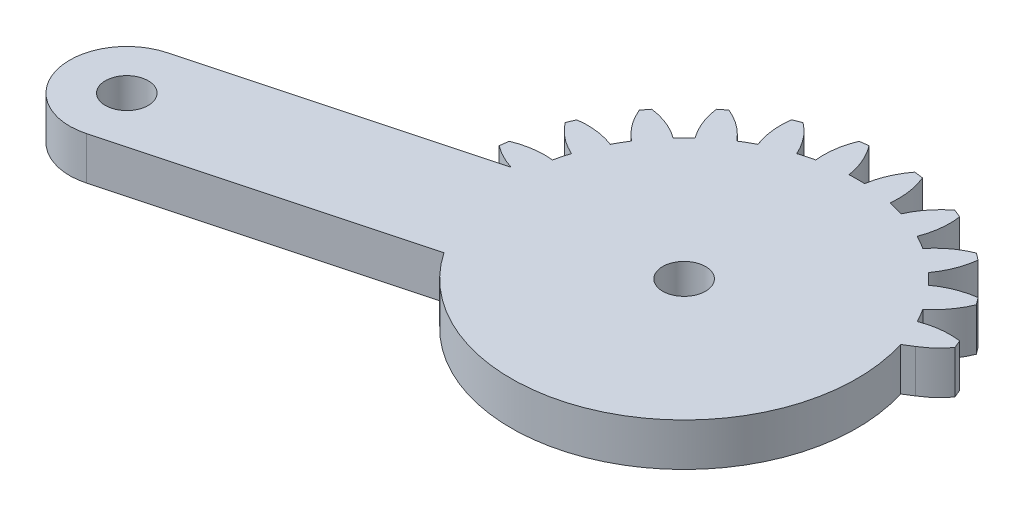
SolidWorks part; units mm, degrees
ref_plane "Front Plane" through (0, 0, 0) normal (0, 0, 1) x (1, 0, 0)
ref_plane "Top Plane" through (0, 0, 0) normal (0, 1, 0) x (1, 0, 0)
ref_plane "Right Plane" through (0, 0, 0) normal (1, 0, 0) x (0, 0, -1)
sketch "Sketch1" plane through (0, 0, 0) normal (0, 1, 0) x (1, 0, 0)
  line L0 (20.6437, 4) -> (2.0816, 4)
  line L1 (2.0816, -4) -> (20.6437, -4)
  arc A0 (2.0816, 4) -> (3.5217, 5.3071) centre (-0.7683, 8.5867) ccw
  arc A1 (3.5217, 5.3071) -> (3.2829, 5.8838) centre (-10.1063, 0) ccw
  arc A2 (3.2829, 5.8838) -> (0.6271, 5.5703) centre (2.5684, 0.5313) ccw
  arc A3 (0.6271, 5.5703) -> (0.0844, 6.5103) centre (-10.1063, 0) ccw
  arc A4 (0.0844, 6.5103) -> (1.6838, 8.6535) centre (-3.3089, 10.711) ccw
  arc A5 (1.6838, 8.6535) -> (1.3038, 9.1487) centre (-10.1063, 0) ccw
  arc A6 (1.3038, 9.1487) -> (-1.1803, 8.1585) centre (1.999, 3.7936) ccw
  arc A7 (-1.1803, 8.1585) -> (-1.9479, 8.926) centre (-10.1063, 0) ccw
  arc A8 (-1.9479, 8.926) -> (-0.9576, 11.4102) centre (-6.3127, 12.1053) ccw
  arc A9 (-0.9576, 11.4102) -> (-1.4528, 11.7901) centre (-10.1063, 0) ccw
  arc A10 (-1.4528, 11.7901) -> (-3.596, 10.1907) centre (0.6046, 6.7975) ccw
  arc A11 (-3.596, 10.1907) -> (-4.5361, 10.7334) centre (-10.1063, 0) ccw
  arc A12 (-4.5361, 10.7334) -> (-4.2225, 13.3892) centre (-9.5751, 12.6747) ccw
  arc A13 (-4.2225, 13.3892) -> (-4.7992, 13.6281) centre (-10.1063, 0) ccw
  arc A14 (-4.7992, 13.6281) -> (-6.4554, 11.5285) centre (-1.5196, 9.3381) ccw
  arc A15 (-6.4554, 11.5285) -> (-7.5039, 11.8094) centre (-10.1063, 0) ccw
  arc A16 (-7.5039, 11.8094) -> (-7.8884, 14.4558) centre (-12.8736, 12.3803) ccw
  arc A17 (-7.8884, 14.4558) -> (-8.5072, 14.5373) centre (-10.1063, 0) ccw
  arc A18 (-8.5072, 14.5373) -> (-9.5636, 12.0806) centre (-4.2291, 11.2423) ccw
  arc A19 (-9.5636, 12.0806) -> (-10.6491, 12.0806) centre (-10.1063, 0) ccw
  arc A20 (-10.6491, 12.0806) -> (-11.7054, 14.5373) centre (-15.9836, 11.2423) ccw
  arc A21 (-11.7054, 14.5373) -> (-12.3243, 14.4558) centre (-10.1063, 0) ccw
  arc A22 (-12.3243, 14.4558) -> (-12.7088, 11.8094) centre (-7.3391, 12.3803) ccw
  arc A23 (-12.7088, 11.8094) -> (-13.7573, 11.5285) centre (-10.1063, 0) ccw
  arc A24 (-13.7573, 11.5285) -> (-15.4135, 13.6281) centre (-18.6931, 9.3381) ccw
  arc A25 (-15.4135, 13.6281) -> (-15.9901, 13.3892) centre (-10.1063, 0) ccw
  arc A26 (-15.9901, 13.3892) -> (-15.6766, 10.7334) centre (-10.6376, 12.6747) ccw
  arc A27 (-15.6766, 10.7334) -> (-16.6166, 10.1907) centre (-10.1063, 0) ccw
  arc A28 (-16.6166, 10.1907) -> (-18.7599, 11.7901) centre (-20.8173, 6.7975) ccw
  arc A29 (-18.7599, 11.7901) -> (-19.255, 11.4102) centre (-10.1063, 0) ccw
  arc A30 (-19.255, 11.4102) -> (-18.2648, 8.926) centre (-13.9, 12.1053) ccw
  arc A31 (-18.2648, 8.926) -> (-19.0324, 8.1585) centre (-10.1063, 0) ccw
  arc A32 (-19.0324, 8.1585) -> (-21.5165, 9.1487) centre (-22.2117, 3.7936) ccw
  arc A33 (-21.5165, 9.1487) -> (-21.8965, 8.6535) centre (-10.1063, 0) ccw
  arc A34 (-21.8965, 8.6535) -> (-20.2971, 6.5103) centre (-16.9038, 10.711) ccw
  arc A35 (-20.2971, 6.5103) -> (-20.8398, 5.5703) centre (-10.1063, 0) ccw
  arc A36 (-20.8398, 5.5703) -> (-23.4956, 5.8838) centre (-22.7811, 0.5313) ccw
  arc A37 (-23.4956, 5.8838) -> (-23.7344, 5.3071) centre (-10.1063, 0) ccw
  arc A38 (-23.7344, 5.3071) -> (-21.6348, 3.6509) centre (-19.4444, 8.5867) ccw
  arc A39 (-21.6348, 3.6509) -> (-21.9157, 2.6025) centre (-10.1063, 0) ccw
  arc A40 (-21.9157, 2.6025) -> (-24.5622, 2.2179) centre (-22.4867, -2.7673) ccw
  arc A41 (-24.5622, 2.2179) -> (-24.6437, 1.5991) centre (-10.1063, 0) ccw
  arc A42 (-24.6437, 1.5991) -> (-22.1869, 0.5427) centre (-21.3486, 5.8773) ccw
  arc A43 (-22.1869, 0.5427) -> (-22.1869, -0.5427) centre (-10.1063, 0) ccw
  arc A44 (-22.1869, -0.5427) -> (-24.6437, -1.5991) centre (-21.3486, -5.8773) ccw
  arc A45 (-24.6437, -1.5991) -> (-24.5622, -2.2179) centre (-10.1063, 0) ccw
  arc A46 (-24.5622, -2.2179) -> (-21.9157, -2.6025) centre (-22.4867, 2.7673) ccw
  arc A47 (-21.9157, -2.6025) -> (-21.6348, -3.6509) centre (-10.1063, 0) ccw
  arc A48 (-21.6348, -3.6509) -> (-23.7344, -5.3071) centre (-19.4444, -8.5867) ccw
  arc A49 (-23.7344, -5.3071) -> (-23.4956, -5.8838) centre (-10.1063, 0) ccw
  arc A50 (-23.4956, -5.8838) -> (-20.8398, -5.5703) centre (-22.7811, -0.5313) ccw
  arc A51 (-20.8398, -5.5703) -> (-20.2971, -6.5103) centre (-10.1063, 0) ccw
  arc A52 (-20.2971, -6.5103) -> (-21.8965, -8.6535) centre (-16.9038, -10.711) ccw
  arc A53 (-21.8965, -8.6535) -> (-21.5165, -9.1487) centre (-10.1063, 0) ccw
  arc A54 (-21.5165, -9.1487) -> (-19.0324, -8.1585) centre (-22.2117, -3.7936) ccw
  arc A55 (-19.0324, -8.1585) -> (-18.2648, -8.926) centre (-10.1063, 0) ccw
  arc A56 (-18.2648, -8.926) -> (-19.255, -11.4102) centre (-13.9, -12.1053) ccw
  arc A57 (-19.255, -11.4102) -> (-18.7599, -11.7901) centre (-10.1063, 0) ccw
  arc A58 (-18.7599, -11.7901) -> (-16.6166, -10.1907) centre (-20.8173, -6.7975) ccw
  arc A59 (-16.6166, -10.1907) -> (-15.6766, -10.7334) centre (-10.1063, 0) ccw
  arc A60 (-15.6766, -10.7334) -> (-15.9901, -13.3892) centre (-10.6376, -12.6747) ccw
  arc A61 (-15.9901, -13.3892) -> (-15.4135, -13.6281) centre (-10.1063, 0) ccw
  arc A62 (-15.4135, -13.6281) -> (-13.7573, -11.5285) centre (-18.6931, -9.3381) ccw
  arc A63 (-13.7573, -11.5285) -> (-12.7088, -11.8094) centre (-10.1063, 0) ccw
  arc A64 (-12.7088, -11.8094) -> (-12.3243, -14.4558) centre (-7.3391, -12.3803) ccw
  arc A65 (-12.3243, -14.4558) -> (-11.7054, -14.5373) centre (-10.1063, 0) ccw
  arc A66 (-11.7054, -14.5373) -> (-10.6491, -12.0806) centre (-15.9836, -11.2423) ccw
  arc A67 (-10.6491, -12.0806) -> (-9.5636, -12.0806) centre (-10.1063, 0) ccw
  arc A68 (-9.5636, -12.0806) -> (-8.5072, -14.5373) centre (-4.2291, -11.2423) ccw
  arc A69 (-8.5072, -14.5373) -> (-7.8884, -14.4558) centre (-10.1063, 0) ccw
  arc A70 (-7.8884, -14.4558) -> (-7.5039, -11.8094) centre (-12.8736, -12.3803) ccw
  arc A71 (-7.5039, -11.8094) -> (-6.4554, -11.5285) centre (-10.1063, 0) ccw
  arc A72 (-6.4554, -11.5285) -> (-4.7992, -13.6281) centre (-1.5196, -9.3381) ccw
  arc A73 (-4.7992, -13.6281) -> (-4.2225, -13.3892) centre (-10.1063, 0) ccw
  arc A74 (-4.2225, -13.3892) -> (-4.5361, -10.7334) centre (-9.5751, -12.6747) ccw
  arc A75 (-4.5361, -10.7334) -> (-3.596, -10.1907) centre (-10.1063, 0) ccw
  arc A76 (-3.596, -10.1907) -> (-1.4528, -11.7901) centre (0.6046, -6.7975) ccw
  arc A77 (-1.4528, -11.7901) -> (-0.9576, -11.4102) centre (-10.1063, 0) ccw
  arc A78 (-0.9576, -11.4102) -> (-1.9479, -8.926) centre (-6.3127, -12.1053) ccw
  arc A79 (-1.9479, -8.926) -> (-1.1803, -8.1585) centre (-10.1063, 0) ccw
  arc A80 (-1.1803, -8.1585) -> (1.3038, -9.1487) centre (1.999, -3.7936) ccw
  arc A81 (1.3038, -9.1487) -> (1.6838, -8.6535) centre (-10.1063, 0) ccw
  arc A82 (1.6838, -8.6535) -> (0.0844, -6.5103) centre (-3.3089, -10.711) ccw
  arc A83 (0.0844, -6.5103) -> (0.6271, -5.5703) centre (-10.1063, 0) ccw
  arc A84 (0.6271, -5.5703) -> (3.2829, -5.8838) centre (2.5684, -0.5313) ccw
  arc A85 (3.2829, -5.8838) -> (3.5217, -5.3071) centre (-10.1063, 0) ccw
  arc A86 (3.5217, -5.3071) -> (2.0816, -4) centre (-0.7683, -8.5867) ccw
  arc A87 (20.6437, -4) -> (20.6437, 4) centre (20.6437, 0) ccw
  circle A88 centre (-10.1063, 0) radius 1.5
  circle A89 centre (20.6437, 0) radius 1.5
  dimension "D1" = 3
  dimension "D2" = 3
extrude "Boss-Extrude1" add sketch "Sketch1" along normal blind 3
sketch "Sketch3" plane through (0, 3, 0) normal (0, 1, 0) x (1, 0, 0)
  line L0 (-10.1063, 0) -> (-40.8563, 0) construction
  line L1 (-10.1063, 0) -> (-40.8563, -8.2394)
  line L2 (-11.1416, 3.8637) -> (-41.8916, -4.3757)
  line L3 (-9.0711, -3.8637) -> (-39.8211, -12.1031)
  circle A0 centre (-10.1063, 0) radius 1.5
  circle A1 centre (20.6437, 0) radius 1.5 construction
  circle A2 centre (20.6437, 0) radius 1.5
  circle A3 centre (-40.8563, -8.2394) radius 1.5
  circle A4 centre (-40.8563, -8.2394) radius 4
  circle A5 centre (-10.1063, 0) radius 4
  dimension "D2" = 3
  dimension "D5" = 3
  dimension "D6" = 8
  dimension "D7" = 8
  dimension "D1" = 30.75
  dimension "D3" = 30.75
  dimension "D4" = 15
extrude "Boss-Extrude2" add sketch "Sketch3" against normal blind 3
sketch "Sketch4" plane through (0, 3, 0) normal (0, 1, 0) x (1, 0, 0)
  line L0 (20.6437, 4) -> (2.0816, 4) construction
  line L1 (2.0816, -4) -> (20.6437, -4) construction
  line L2 (20.6437, 4) -> (2.0816, 4)
  line L3 (2.0816, -4) -> (20.6437, -4)
  line L4 (2.0816, 4) -> (1.4381, 3.6001)
  line L5 (-20.8438, -7.0182) -> (-20.0942, -6.8174)
  line L8 (-22.9143, 0.7092) -> (-41.8916, -4.3757)
  line L9 (-39.8211, -12.1031) -> (-20.8438, -7.0182)
  line L10 (2.0816, -4) -> (20.6437, -4)
  line L11 (20.6437, 4) -> (2.0816, 4)
  line L12 (-22.9143, 0.7092) -> (-41.8916, -4.3757)
  line L13 (-39.8211, -12.1031) -> (-20.8438, -7.0182)
  line L14 (2.0816, -4) -> (20.6437, -4)
  line L15 (20.6437, 4) -> (2.0816, 4)
  circle A0 centre (-10.1063, 0) radius 12.0927
  arc A1 (3.2829, 5.8838) -> (0.6271, 5.5703) centre (2.5684, 0.5313) ccw construction
  arc A2 (3.5217, 5.3071) -> (3.2829, 5.8838) centre (-10.1063, 0) ccw construction
  arc A3 (2.0816, 4) -> (3.5217, 5.3071) centre (-0.7683, 8.5867) ccw construction
  arc A4 (20.6437, -4) -> (20.6437, 4) centre (20.6437, 0) ccw construction
  arc A5 (3.5217, -5.3071) -> (2.0816, -4) centre (-0.7683, -8.5867) ccw construction
  arc A6 (3.2829, -5.8838) -> (3.5217, -5.3071) centre (-10.1063, 0) ccw construction
  arc A7 (0.6271, -5.5703) -> (3.2829, -5.8838) centre (2.5684, -0.5313) ccw construction
  arc A8 (3.2829, 5.8838) -> (0.6271, 5.5703) centre (2.5684, 0.5313) ccw
  arc A9 (3.5217, 5.3071) -> (3.2829, 5.8838) centre (-10.1063, 0) ccw
  arc A10 (2.0816, 4) -> (3.5217, 5.3071) centre (-0.7683, 8.5867) ccw
  arc A11 (20.6437, -4) -> (20.6437, 4) centre (20.6437, 0) ccw
  arc A12 (3.5217, -5.3071) -> (2.0816, -4) centre (-0.7683, -8.5867) ccw
  arc A13 (3.2829, -5.8838) -> (3.5217, -5.3071) centre (-10.1063, 0) ccw
  arc A14 (0.6271, -5.5703) -> (3.2829, -5.8838) centre (2.5684, -0.5313) ccw
  arc A95 (-24.6437, 1.5991) -> (-22.9143, 0.7092) centre (-21.3486, 5.8773) ccw
  arc A96 (-41.8916, -4.3757) -> (-39.8211, -12.1031) centre (-40.8563, -8.2394) ccw
  arc A97 (-20.8438, -7.0182) -> (-21.8965, -8.6535) centre (-16.9038, -10.711) ccw
  arc A98 (-21.8965, -8.6535) -> (-21.5165, -9.1487) centre (-10.1063, 0) ccw
  arc A99 (-21.5165, -9.1487) -> (-19.0324, -8.1585) centre (-22.2117, -3.7936) ccw
  arc A100 (-19.0324, -8.1585) -> (-18.2648, -8.926) centre (-10.1063, 0) ccw
  arc A101 (-18.2648, -8.926) -> (-19.255, -11.4102) centre (-13.9, -12.1053) ccw
  arc A102 (-19.255, -11.4102) -> (-18.7599, -11.7901) centre (-10.1063, 0) ccw
  arc A103 (-18.7599, -11.7901) -> (-16.6166, -10.1907) centre (-20.8173, -6.7975) ccw
  arc A104 (-16.6166, -10.1907) -> (-15.6766, -10.7334) centre (-10.1063, 0) ccw
  arc A105 (-15.6766, -10.7334) -> (-15.9901, -13.3892) centre (-10.6376, -12.6747) ccw
  arc A106 (-15.9901, -13.3892) -> (-15.4135, -13.6281) centre (-10.1063, 0) ccw
  arc A107 (-15.4135, -13.6281) -> (-13.7573, -11.5285) centre (-18.6931, -9.3381) ccw
  arc A108 (-13.7573, -11.5285) -> (-12.7088, -11.8094) centre (-10.1063, 0) ccw
  arc A109 (-12.7088, -11.8094) -> (-12.3243, -14.4558) centre (-7.3391, -12.3803) ccw
  arc A110 (-12.3243, -14.4558) -> (-11.7054, -14.5373) centre (-10.1063, 0) ccw
  arc A111 (-11.7054, -14.5373) -> (-10.6491, -12.0806) centre (-15.9836, -11.2423) ccw
  arc A112 (-10.6491, -12.0806) -> (-9.5636, -12.0806) centre (-10.1063, 0) ccw
  arc A113 (-9.5636, -12.0806) -> (-8.5072, -14.5373) centre (-4.2291, -11.2423) ccw
  arc A114 (-8.5072, -14.5373) -> (-7.8884, -14.4558) centre (-10.1063, 0) ccw
  arc A115 (-7.8884, -14.4558) -> (-7.5039, -11.8094) centre (-12.8736, -12.3803) ccw
  arc A116 (-7.5039, -11.8094) -> (-6.4554, -11.5285) centre (-10.1063, 0) ccw
  arc A117 (-6.4554, -11.5285) -> (-4.7992, -13.6281) centre (-1.5196, -9.3381) ccw
  arc A118 (-4.7992, -13.6281) -> (-4.2225, -13.3892) centre (-10.1063, 0) ccw
  arc A119 (-4.2225, -13.3892) -> (-4.5361, -10.7334) centre (-9.5751, -12.6747) ccw
  arc A120 (-4.5361, -10.7334) -> (-3.596, -10.1907) centre (-10.1063, 0) ccw
  arc A121 (-3.596, -10.1907) -> (-1.4528, -11.7901) centre (0.6046, -6.7975) ccw
  arc A122 (-1.4528, -11.7901) -> (-0.9576, -11.4102) centre (-10.1063, 0) ccw
  arc A123 (-0.9576, -11.4102) -> (-1.9479, -8.926) centre (-6.3127, -12.1053) ccw
  arc A124 (-1.9479, -8.926) -> (-1.1803, -8.1585) centre (-10.1063, 0) ccw
  arc A125 (-1.1803, -8.1585) -> (1.3038, -9.1487) centre (1.999, -3.7936) ccw
  arc A126 (1.3038, -9.1487) -> (1.6838, -8.6535) centre (-10.1063, 0) ccw
  arc A127 (1.6838, -8.6535) -> (0.0844, -6.5103) centre (-3.3089, -10.711) ccw
  arc A128 (0.0844, -6.5103) -> (0.6271, -5.5703) centre (-10.1063, 0) ccw
  arc A129 (0.6271, -5.5703) -> (3.2829, -5.8838) centre (2.5684, -0.5313) ccw
  arc A130 (3.2829, -5.8838) -> (3.5217, -5.3071) centre (-10.1063, 0) ccw
  arc A131 (3.5217, -5.3071) -> (2.0816, -4) centre (-0.7683, -8.5867) ccw
  arc A132 (20.6437, -4) -> (20.6437, 4) centre (20.6437, 0) ccw
  arc A133 (2.0816, 4) -> (3.5217, 5.3071) centre (-0.7683, 8.5867) ccw
  arc A134 (3.5217, 5.3071) -> (3.2829, 5.8838) centre (-10.1063, 0) ccw
  arc A135 (3.2829, 5.8838) -> (0.6271, 5.5703) centre (2.5684, 0.5313) ccw
  arc A136 (0.6271, 5.5703) -> (0.0844, 6.5103) centre (-10.1063, 0) ccw
  arc A137 (0.0844, 6.5103) -> (1.6838, 8.6535) centre (-3.3089, 10.711) ccw
  arc A138 (1.6838, 8.6535) -> (1.3038, 9.1487) centre (-10.1063, 0) ccw
  arc A139 (1.3038, 9.1487) -> (-1.1803, 8.1585) centre (1.999, 3.7936) ccw
  arc A140 (-1.1803, 8.1585) -> (-1.9479, 8.926) centre (-10.1063, 0) ccw
  arc A141 (-1.9479, 8.926) -> (-0.9576, 11.4102) centre (-6.3127, 12.1053) ccw
  arc A142 (-0.9576, 11.4102) -> (-1.4528, 11.7901) centre (-10.1063, 0) ccw
  arc A143 (-1.4528, 11.7901) -> (-3.596, 10.1907) centre (0.6046, 6.7975) ccw
  arc A144 (-3.596, 10.1907) -> (-4.5361, 10.7334) centre (-10.1063, 0) ccw
  arc A145 (-4.5361, 10.7334) -> (-4.2225, 13.3892) centre (-9.5751, 12.6747) ccw
  arc A146 (-4.2225, 13.3892) -> (-4.7992, 13.6281) centre (-10.1063, 0) ccw
  arc A147 (-4.7992, 13.6281) -> (-6.4554, 11.5285) centre (-1.5196, 9.3381) ccw
  arc A148 (-6.4554, 11.5285) -> (-7.5039, 11.8094) centre (-10.1063, 0) ccw
  arc A149 (-7.5039, 11.8094) -> (-7.8884, 14.4558) centre (-12.8736, 12.3803) ccw
  arc A150 (-7.8884, 14.4558) -> (-8.5072, 14.5373) centre (-10.1063, 0) ccw
  arc A151 (-8.5072, 14.5373) -> (-9.5636, 12.0806) centre (-4.2291, 11.2423) ccw
  arc A152 (-9.5636, 12.0806) -> (-10.6491, 12.0806) centre (-10.1063, 0) ccw
  arc A153 (-10.6491, 12.0806) -> (-11.7054, 14.5373) centre (-15.9836, 11.2423) ccw
  arc A154 (-11.7054, 14.5373) -> (-12.3243, 14.4558) centre (-10.1063, 0) ccw
  arc A155 (-12.3243, 14.4558) -> (-12.7088, 11.8094) centre (-7.3391, 12.3803) ccw
  arc A156 (-12.7088, 11.8094) -> (-13.7573, 11.5285) centre (-10.1063, 0) ccw
  arc A157 (-13.7573, 11.5285) -> (-15.4135, 13.6281) centre (-18.6931, 9.3381) ccw
  arc A158 (-15.4135, 13.6281) -> (-15.9901, 13.3892) centre (-10.1063, 0) ccw
  arc A159 (-15.9901, 13.3892) -> (-15.6766, 10.7334) centre (-10.6376, 12.6747) ccw
  arc A160 (-15.6766, 10.7334) -> (-16.6166, 10.1907) centre (-10.1063, 0) ccw
  arc A161 (-16.6166, 10.1907) -> (-18.7599, 11.7901) centre (-20.8173, 6.7975) ccw
  arc A162 (-18.7599, 11.7901) -> (-19.255, 11.4102) centre (-10.1063, 0) ccw
  arc A163 (-19.255, 11.4102) -> (-18.2648, 8.926) centre (-13.9, 12.1053) ccw
  arc A164 (-18.2648, 8.926) -> (-19.0324, 8.1585) centre (-10.1063, 0) ccw
  arc A165 (-19.0324, 8.1585) -> (-21.5165, 9.1487) centre (-22.2117, 3.7936) ccw
  arc A166 (-21.5165, 9.1487) -> (-21.8965, 8.6535) centre (-10.1063, 0) ccw
  arc A167 (-21.8965, 8.6535) -> (-20.2971, 6.5103) centre (-16.9038, 10.711) ccw
  arc A168 (-20.2971, 6.5103) -> (-20.8398, 5.5703) centre (-10.1063, 0) ccw
  arc A169 (-20.8398, 5.5703) -> (-23.4956, 5.8838) centre (-22.7811, 0.5313) ccw
  arc A170 (-23.4956, 5.8838) -> (-23.7344, 5.3071) centre (-10.1063, 0) ccw
  arc A171 (-23.7344, 5.3071) -> (-21.6348, 3.6509) centre (-19.4444, 8.5867) ccw
  arc A172 (-21.6348, 3.6509) -> (-21.9157, 2.6025) centre (-10.1063, 0) ccw
  arc A173 (-21.9157, 2.6025) -> (-24.5622, 2.2179) centre (-22.4867, -2.7673) ccw
  arc A174 (-24.5622, 2.2179) -> (-24.6437, 1.5991) centre (-10.1063, 0) ccw
  arc A175 (-24.6437, 1.5991) -> (-22.9143, 0.7092) centre (-21.3486, 5.8773) ccw
  arc A176 (-41.8916, -4.3757) -> (-39.8211, -12.1031) centre (-40.8563, -8.2394) ccw
  arc A177 (-20.8438, -7.0182) -> (-21.8965, -8.6535) centre (-16.9038, -10.711) ccw
  arc A178 (-21.8965, -8.6535) -> (-21.5165, -9.1487) centre (-10.1063, 0) ccw
  arc A179 (-21.5165, -9.1487) -> (-19.0324, -8.1585) centre (-22.2117, -3.7936) ccw
  arc A180 (-19.0324, -8.1585) -> (-18.2648, -8.926) centre (-10.1063, 0) ccw
  arc A181 (-18.2648, -8.926) -> (-19.255, -11.4102) centre (-13.9, -12.1053) ccw
  arc A182 (-19.255, -11.4102) -> (-18.7599, -11.7901) centre (-10.1063, 0) ccw
  arc A183 (-18.7599, -11.7901) -> (-16.6166, -10.1907) centre (-20.8173, -6.7975) ccw
  arc A184 (-16.6166, -10.1907) -> (-15.6766, -10.7334) centre (-10.1063, 0) ccw
  arc A185 (-15.6766, -10.7334) -> (-15.9901, -13.3892) centre (-10.6376, -12.6747) ccw
  arc A186 (-15.9901, -13.3892) -> (-15.4135, -13.6281) centre (-10.1063, 0) ccw
  arc A187 (-15.4135, -13.6281) -> (-13.7573, -11.5285) centre (-18.6931, -9.3381) ccw
  arc A188 (-13.7573, -11.5285) -> (-12.7088, -11.8094) centre (-10.1063, 0) ccw
  arc A189 (-12.7088, -11.8094) -> (-12.3243, -14.4558) centre (-7.3391, -12.3803) ccw
  arc A190 (-12.3243, -14.4558) -> (-11.7054, -14.5373) centre (-10.1063, 0) ccw
  arc A191 (-11.7054, -14.5373) -> (-10.6491, -12.0806) centre (-15.9836, -11.2423) ccw
  arc A192 (-10.6491, -12.0806) -> (-9.5636, -12.0806) centre (-10.1063, 0) ccw
  arc A193 (-9.5636, -12.0806) -> (-8.5072, -14.5373) centre (-4.2291, -11.2423) ccw
  arc A194 (-8.5072, -14.5373) -> (-7.8884, -14.4558) centre (-10.1063, 0) ccw
  arc A195 (-7.8884, -14.4558) -> (-7.5039, -11.8094) centre (-12.8736, -12.3803) ccw
  arc A196 (-7.5039, -11.8094) -> (-6.4554, -11.5285) centre (-10.1063, 0) ccw
  arc A197 (-6.4554, -11.5285) -> (-4.7992, -13.6281) centre (-1.5196, -9.3381) ccw
  arc A198 (-4.7992, -13.6281) -> (-4.2225, -13.3892) centre (-10.1063, 0) ccw
  arc A199 (-4.2225, -13.3892) -> (-4.5361, -10.7334) centre (-9.5751, -12.6747) ccw
  arc A200 (-4.5361, -10.7334) -> (-3.596, -10.1907) centre (-10.1063, 0) ccw
  arc A201 (-3.596, -10.1907) -> (-1.4528, -11.7901) centre (0.6046, -6.7975) ccw
  arc A202 (-1.4528, -11.7901) -> (-0.9576, -11.4102) centre (-10.1063, 0) ccw
  arc A203 (-0.9576, -11.4102) -> (-1.9479, -8.926) centre (-6.3127, -12.1053) ccw
  arc A204 (-1.9479, -8.926) -> (-1.1803, -8.1585) centre (-10.1063, 0) ccw
  arc A205 (-1.1803, -8.1585) -> (1.3038, -9.1487) centre (1.999, -3.7936) ccw
  arc A206 (1.3038, -9.1487) -> (1.6838, -8.6535) centre (-10.1063, 0) ccw
  arc A207 (1.6838, -8.6535) -> (0.0844, -6.5103) centre (-3.3089, -10.711) ccw
  arc A208 (0.0844, -6.5103) -> (0.6271, -5.5703) centre (-10.1063, 0) ccw
  arc A209 (0.6271, -5.5703) -> (3.2829, -5.8838) centre (2.5684, -0.5313) ccw
  arc A210 (3.2829, -5.8838) -> (3.5217, -5.3071) centre (-10.1063, 0) ccw
  arc A211 (3.5217, -5.3071) -> (2.0816, -4) centre (-0.7683, -8.5867) ccw
  arc A212 (20.6437, -4) -> (20.6437, 4) centre (20.6437, 0) ccw
  arc A213 (2.0816, 4) -> (3.5217, 5.3071) centre (-0.7683, 8.5867) ccw
  arc A214 (3.5217, 5.3071) -> (3.2829, 5.8838) centre (-10.1063, 0) ccw
  arc A215 (3.2829, 5.8838) -> (0.6271, 5.5703) centre (2.5684, 0.5313) ccw
  arc A216 (0.6271, 5.5703) -> (0.0844, 6.5103) centre (-10.1063, 0) ccw
  arc A217 (0.0844, 6.5103) -> (1.6838, 8.6535) centre (-3.3089, 10.711) ccw
  arc A218 (1.6838, 8.6535) -> (1.3038, 9.1487) centre (-10.1063, 0) ccw
  arc A219 (1.3038, 9.1487) -> (-1.1803, 8.1585) centre (1.999, 3.7936) ccw
  arc A220 (-1.1803, 8.1585) -> (-1.9479, 8.926) centre (-10.1063, 0) ccw
  arc A221 (-1.9479, 8.926) -> (-0.9576, 11.4102) centre (-6.3127, 12.1053) ccw
  arc A222 (-0.9576, 11.4102) -> (-1.4528, 11.7901) centre (-10.1063, 0) ccw
  arc A223 (-1.4528, 11.7901) -> (-3.596, 10.1907) centre (0.6046, 6.7975) ccw
  arc A224 (-3.596, 10.1907) -> (-4.5361, 10.7334) centre (-10.1063, 0) ccw
  arc A225 (-4.5361, 10.7334) -> (-4.2225, 13.3892) centre (-9.5751, 12.6747) ccw
  arc A226 (-4.2225, 13.3892) -> (-4.7992, 13.6281) centre (-10.1063, 0) ccw
  arc A227 (-4.7992, 13.6281) -> (-6.4554, 11.5285) centre (-1.5196, 9.3381) ccw
  arc A228 (-6.4554, 11.5285) -> (-7.5039, 11.8094) centre (-10.1063, 0) ccw
  arc A229 (-7.5039, 11.8094) -> (-7.8884, 14.4558) centre (-12.8736, 12.3803) ccw
  arc A230 (-7.8884, 14.4558) -> (-8.5072, 14.5373) centre (-10.1063, 0) ccw
  arc A231 (-8.5072, 14.5373) -> (-9.5636, 12.0806) centre (-4.2291, 11.2423) ccw
  arc A232 (-9.5636, 12.0806) -> (-10.6491, 12.0806) centre (-10.1063, 0) ccw
  arc A233 (-10.6491, 12.0806) -> (-11.7054, 14.5373) centre (-15.9836, 11.2423) ccw
  arc A234 (-11.7054, 14.5373) -> (-12.3243, 14.4558) centre (-10.1063, 0) ccw
  arc A235 (-12.3243, 14.4558) -> (-12.7088, 11.8094) centre (-7.3391, 12.3803) ccw
  arc A236 (-12.7088, 11.8094) -> (-13.7573, 11.5285) centre (-10.1063, 0) ccw
  arc A237 (-13.7573, 11.5285) -> (-15.4135, 13.6281) centre (-18.6931, 9.3381) ccw
  arc A238 (-15.4135, 13.6281) -> (-15.9901, 13.3892) centre (-10.1063, 0) ccw
  arc A239 (-15.9901, 13.3892) -> (-15.6766, 10.7334) centre (-10.6376, 12.6747) ccw
  arc A240 (-15.6766, 10.7334) -> (-16.6166, 10.1907) centre (-10.1063, 0) ccw
  arc A241 (-16.6166, 10.1907) -> (-18.7599, 11.7901) centre (-20.8173, 6.7975) ccw
  arc A242 (-18.7599, 11.7901) -> (-19.255, 11.4102) centre (-10.1063, 0) ccw
  arc A243 (-19.255, 11.4102) -> (-18.2648, 8.926) centre (-13.9, 12.1053) ccw
  arc A244 (-18.2648, 8.926) -> (-19.0324, 8.1585) centre (-10.1063, 0) ccw
  arc A245 (-19.0324, 8.1585) -> (-21.5165, 9.1487) centre (-22.2117, 3.7936) ccw
  arc A246 (-21.5165, 9.1487) -> (-21.8965, 8.6535) centre (-10.1063, 0) ccw
  arc A247 (-21.8965, 8.6535) -> (-20.2971, 6.5103) centre (-16.9038, 10.711) ccw
  arc A248 (-20.2971, 6.5103) -> (-20.8398, 5.5703) centre (-10.1063, 0) ccw
  arc A249 (-20.8398, 5.5703) -> (-23.4956, 5.8838) centre (-22.7811, 0.5313) ccw
  arc A250 (-23.4956, 5.8838) -> (-23.7344, 5.3071) centre (-10.1063, 0) ccw
  arc A251 (-23.7344, 5.3071) -> (-21.6348, 3.6509) centre (-19.4444, 8.5867) ccw
  arc A252 (-21.6348, 3.6509) -> (-21.9157, 2.6025) centre (-10.1063, 0) ccw
  arc A253 (-21.9157, 2.6025) -> (-24.5622, 2.2179) centre (-22.4867, -2.7673) ccw
  arc A254 (-24.5622, 2.2179) -> (-24.6437, 1.5991) centre (-10.1063, 0) ccw
  dimension "D2" = 24.1855
  dimension "D1" = 0
extrude "Cut-Extrude1" cut sketch "Sketch4" against normal blind 3 contours A178 A179 A0 L5 A177 | A182 A183 A0 A181 | A186 A187 A0 A185 | A190 A191 A0 A189 | A194 A195 A0 A193 | A198 A199 A0 A197 | A202 A203 A0 A201 | A206 A207 A0 A205 | A0 A14 A13 A12 L3 A11 L2 L4
sketch "Sketch5" plane through (0, 3, 0) normal (0, 1, 0) x (1, 0, 0)
  line L0 (-10.1063, 0) -> (-3.6444, 3.2768)
